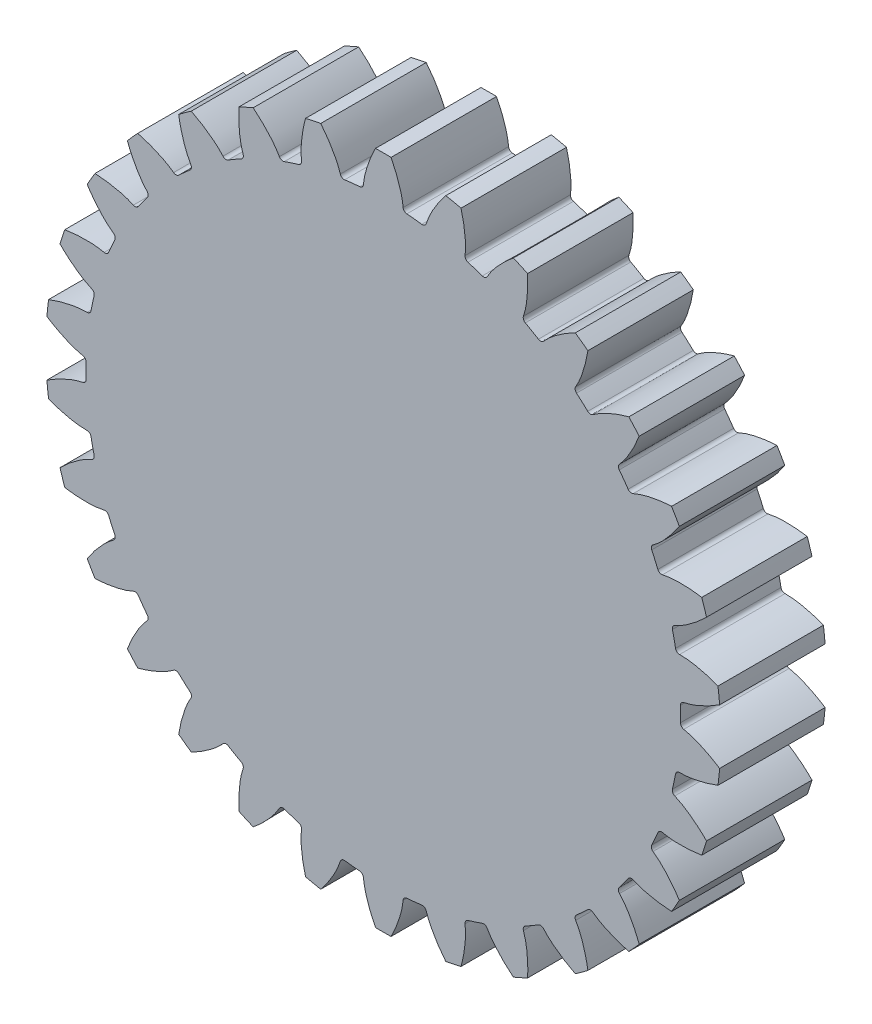
SolidWorks part; units mm, degrees
ref_plane "前视基准面" through (0, 0, 0) normal (0, 0, 1) x (1, 0, 0)
ref_plane "上视基准面" through (0, 0, 0) normal (0, 1, 0) x (1, 0, 0)
ref_plane "右视基准面" through (0, 0, 0) normal (1, 0, 0) x (0, 0, -1)
other "Configuration Table"
sketch "circles" plane through (0, 0, 0) normal (0, 0, 1) x (1, 0, 0)
  circle A0 centre (0, 0) radius 32
  circle A1 centre (0, 0) radius 27.5
  circle A2 centre (0, 0) radius 28.1908
  circle A3 centre (0, 0) radius 30
  dimension "D1" = 60
  dimension "D2" = 56.3816
  dimension "D3" = 55
  dimension "D4" = 64
extrude "Gear_extrude" add sketch "circles" along normal blind 10 contours A0
sketch "Involute" plane through (0, 0, 10) normal (0, 0, 1) x (1, 0, 0)
  spline S0 degree 4 poles (28.171, -1.0557) (28.2223, -1.0593) (28.3658, -1.0748) (28.6344, -1.1247) (29.0665, -1.2353) (29.6059, -1.4183) (30.2862, -1.7021) (31.0629, -2.0956) (31.8862, -2.5882) (32.9602, -3.3359) (34.1728, -4.337) (35.451, -5.5998) (36.7769, -7.1739) (37.9681, -8.8517) (39.0285, -10.6149) (39.9764, -12.4839) (40.7958, -14.4124) (41.4038, -16.142) (41.8493, -17.6484) (42.1713, -18.9171) (42.3998, -19.9389) (42.6495, -21.2237) (42.8522, -22.517) (43.0089, -23.8165) (43.1207, -25.1207) (43.1836, -26.1655) (43.2157, -27.0819) (43.2272, -27.8657) (43.226, -28.5232) (43.2194, -29.0333) (43.2013, -29.7091) (43.1793, -30.2472) (43.1275, -31.2203) (43.075, -31.832) (43.0114, -32.5795) (42.9682, -32.9515) (42.9431, -33.1951) (42.9309, -33.297) knots 0 0 0 0 0 0.005377 0.015084 0.028532 0.04661 0.064855 0.092111 0.119476 0.146842 0.201575 0.256307 0.307035 0.361767 0.4165 0.471232 0.525964 0.580697 0.608063 0.635429 0.662795 0.690161 0.744894 0.77226 0.799626 0.826992 0.854358 0.868042 0.881725 0.895408 0.909091 0.931818 0.954545 0.977273 0.988636 1 1 1 1 1 construction
  spline S2 degree 4 poles (28.171, 1.0557) (28.2223, 1.0593) (28.3658, 1.0748) (28.6344, 1.1247) (29.0665, 1.2353) (29.6059, 1.4183) (30.2862, 1.7021) (31.0629, 2.0956) (31.8862, 2.5882) (32.9602, 3.3359) (34.1728, 4.337) (35.451, 5.5998) (36.7769, 7.1739) (37.9681, 8.8517) (39.0285, 10.6149) (39.9764, 12.4839) (40.7958, 14.4124) (41.4038, 16.142) (41.8493, 17.6484) (42.1713, 18.9171) (42.3998, 19.9389) (42.6495, 21.2237) (42.8522, 22.517) (43.0089, 23.8165) (43.1207, 25.1207) (43.1836, 26.1655) (43.2157, 27.0819) (43.2272, 27.8657) (43.226, 28.5232) (43.2194, 29.0333) (43.2013, 29.7091) (43.1793, 30.2472) (43.1275, 31.2203) (43.075, 31.832) (43.0114, 32.5795) (42.9682, 32.9515) (42.9431, 33.1951) (42.9309, 33.297) knots 0 0 0 0 0 0.005377 0.015084 0.028532 0.04661 0.064855 0.092111 0.119476 0.146842 0.201575 0.256307 0.307035 0.361767 0.4165 0.471232 0.525964 0.580697 0.608063 0.635429 0.662795 0.690161 0.744894 0.77226 0.799626 0.826992 0.854358 0.868042 0.881725 0.895408 0.909091 0.931818 0.954545 0.977273 0.988636 1 1 1 1 1 construction
  spline S3 degree 4 poles (28.171, 1.0557) (28.2223, 1.0593) (28.3658, 1.0748) (28.6344, 1.1247) (29.0665, 1.2353) (29.6059, 1.4183) (30.2862, 1.7021) (31.0629, 2.0956) (31.8862, 2.5882) (32.9602, 3.3359) (34.1728, 4.337) (35.451, 5.5998) (36.7769, 7.1739) (37.9681, 8.8517) (39.0285, 10.6149) (39.9764, 12.4839) (40.7958, 14.4124) (41.4038, 16.142) (41.8493, 17.6484) (42.1713, 18.9171) (42.3998, 19.9389) (42.6495, 21.2237) (42.8522, 22.517) (43.0089, 23.8165) (43.1207, 25.1207) (43.1836, 26.1655) (43.2157, 27.0819) (43.2272, 27.8657) (43.226, 28.5232) (43.2194, 29.0333) (43.2078, 29.4683) (43.1997, 29.7103) (43.1953, 29.8292) knots 0 0 0 0 0 0.005377 0.015084 0.028532 0.04661 0.064855 0.092111 0.119476 0.146842 0.201575 0.256307 0.307035 0.361767 0.4165 0.471232 0.525964 0.580697 0.608063 0.635429 0.662795 0.690161 0.744894 0.77226 0.799626 0.826992 0.854358 0.868042 0.881725 0.895408 0.909091 0.909091 0.909091 0.909091 0.909091
  spline S4 degree 4 poles (28.171, -1.0557) (28.2223, -1.0593) (28.3658, -1.0748) (28.6344, -1.1247) (29.0665, -1.2353) (29.6059, -1.4183) (30.2862, -1.7021) (31.0629, -2.0956) (31.8862, -2.5882) (32.9602, -3.3359) (34.1728, -4.337) (35.451, -5.5998) (36.7769, -7.1739) (37.9681, -8.8517) (39.0285, -10.6149) (39.9764, -12.4839) (40.7958, -14.4124) (41.4038, -16.142) (41.8493, -17.6484) (42.1713, -18.9171) (42.3998, -19.9389) (42.6495, -21.2237) (42.8522, -22.517) (43.0089, -23.8165) (43.1207, -25.1207) (43.1836, -26.1655) (43.2157, -27.0819) (43.2272, -27.8657) (43.226, -28.5232) (43.2194, -29.0333) (43.2078, -29.4683) (43.1997, -29.7103) (43.1953, -29.8292) knots 0 0 0 0 0 0.005377 0.015084 0.028532 0.04661 0.064855 0.092111 0.119476 0.146842 0.201575 0.256307 0.307035 0.361767 0.4165 0.471232 0.525964 0.580697 0.608063 0.635429 0.662795 0.690161 0.744894 0.77226 0.799626 0.826992 0.854358 0.868042 0.881725 0.895408 0.909091 0.909091 0.909091 0.909091 0.909091
sketch "Db>Df" plane through (0, 0, 10) normal (0, 0, 1) x (1, 0, 0)
  line L2 (0, 0) -> (29.9589, 1.5701) construction
  line L3 (0, 0) -> (60.2478, -1.5776) construction
  line L4 (43.1953, 29.8292) -> (60.2478, -1.5776)
  line L5 (60.2478, -1.5776) -> (43.1953, -29.8292)
  circle A2 centre (0, 0) radius 30 construction
  circle A3 centre (0, 0) radius 28.1908 construction
  arc A4 (28.171, -1.0557) -> (28.171, 1.0557) centre (0, 0) ccw
  spline S0 degree 4 poles (-58.7454, -1999.1168) (17.076, -52.2104) (22.5891, -1.8433) (25.9954, -0.4491) (29.0665, -1.2353) (29.6059, -1.4183) (30.2862, -1.7021) (31.0629, -2.0956) (31.8862, -2.5882) (32.9602, -3.3359) (34.1728, -4.337) (35.451, -5.5998) (36.7769, -7.1739) (37.9681, -8.8517) (39.0285, -10.6149) (39.9764, -12.4839) (40.7958, -14.4124) (41.4038, -16.142) (41.8493, -17.6484) (42.1713, -18.9171) (42.3998, -19.9389) (42.6495, -21.2237) (42.8522, -22.517) (43.0089, -23.8165) (43.1207, -25.1207) (43.1836, -26.1655) (43.2157, -27.0819) (43.2272, -27.8657) (43.226, -28.5232) (43.1903, -31.2711) (42.8434, -36.3545) (44.7406, 23.1759) (-32.5965, -2028.0551) knots -0.284666 -0.284666 -0.284666 -0.284666 -0.284666 0.005377 0.015084 0.028532 0.04661 0.064855 0.092111 0.119476 0.146842 0.201575 0.256307 0.307035 0.361767 0.4165 0.471232 0.525964 0.580697 0.608063 0.635429 0.662795 0.690161 0.744894 0.77226 0.799626 0.826992 0.854358 0.868042 0.881725 0.895408 1.149228 1.149228 1.149228 1.149228 1.149228 only from (28.171, -1.0557) to (43.1953, -29.8292) construction
  spline S1 degree 4 poles (-58.7454, 1999.1168) (17.076, 52.2104) (22.5891, 1.8433) (25.9954, 0.4491) (29.0665, 1.2353) (29.6059, 1.4183) (30.2862, 1.7021) (31.0629, 2.0956) (31.8862, 2.5882) (32.9602, 3.3359) (34.1728, 4.337) (35.451, 5.5998) (36.7769, 7.1739) (37.9681, 8.8517) (39.0285, 10.6149) (39.9764, 12.4839) (40.7958, 14.4124) (41.4038, 16.142) (41.8493, 17.6484) (42.1713, 18.9171) (42.3998, 19.9389) (42.6495, 21.2237) (42.8522, 22.517) (43.0089, 23.8165) (43.1207, 25.1207) (43.1836, 26.1655) (43.2157, 27.0819) (43.2272, 27.8657) (43.226, 28.5232) (43.1903, 31.2711) (42.8434, 36.3545) (44.7406, -23.1759) (-32.5965, 2028.0551) knots -0.284666 -0.284666 -0.284666 -0.284666 -0.284666 0.005377 0.015084 0.028532 0.04661 0.064855 0.092111 0.119476 0.146842 0.201575 0.256307 0.307035 0.361767 0.4165 0.471232 0.525964 0.580697 0.608063 0.635429 0.662795 0.690161 0.744894 0.77226 0.799626 0.826992 0.854358 0.868042 0.881725 0.895408 1.149228 1.149228 1.149228 1.149228 1.149228 only from (28.171, 1.0557) to (43.1953, 29.8292) construction
  spline S2 degree 4 poles (28.171, -1.0557) (28.2223, -1.0593) (28.3658, -1.0748) (28.6344, -1.1247) (29.0665, -1.2353) (29.6059, -1.4183) (30.2862, -1.7021) (31.0629, -2.0956) (31.8862, -2.5882) (32.9602, -3.3359) (34.1728, -4.337) (35.451, -5.5998) (36.7769, -7.1739) (37.9681, -8.8517) (39.0285, -10.6149) (39.9764, -12.4839) (40.7958, -14.4124) (41.4038, -16.142) (41.8493, -17.6484) (42.1713, -18.9171) (42.3998, -19.9389) (42.6495, -21.2237) (42.8522, -22.517) (43.0089, -23.8165) (43.1207, -25.1207) (43.1836, -26.1655) (43.2157, -27.0819) (43.2272, -27.8657) (43.226, -28.5232) (43.2194, -29.0333) (43.2078, -29.4683) (43.1997, -29.7103) (43.1953, -29.8292) knots 0 0 0 0 0 0.005377 0.015084 0.028532 0.04661 0.064855 0.092111 0.119476 0.146842 0.201575 0.256307 0.307035 0.361767 0.4165 0.471232 0.525964 0.580697 0.608063 0.635429 0.662795 0.690161 0.744894 0.77226 0.799626 0.826992 0.854358 0.868042 0.881725 0.895408 0.909091 0.909091 0.909091 0.909091 0.909091
  spline S3 degree 4 poles (28.171, 1.0557) (28.2223, 1.0593) (28.3658, 1.0748) (28.6344, 1.1247) (29.0665, 1.2353) (29.6059, 1.4183) (30.2862, 1.7021) (31.0629, 2.0956) (31.8862, 2.5882) (32.9602, 3.3359) (34.1728, 4.337) (35.451, 5.5998) (36.7769, 7.1739) (37.9681, 8.8517) (39.0285, 10.6149) (39.9764, 12.4839) (40.7958, 14.4124) (41.4038, 16.142) (41.8493, 17.6484) (42.1713, 18.9171) (42.3998, 19.9389) (42.6495, 21.2237) (42.8522, 22.517) (43.0089, 23.8165) (43.1207, 25.1207) (43.1836, 26.1655) (43.2157, 27.0819) (43.2272, 27.8657) (43.226, 28.5232) (43.2194, 29.0333) (43.2078, 29.4683) (43.1997, 29.7103) (43.1953, 29.8292) knots 0 0 0 0 0 0.005377 0.015084 0.028532 0.04661 0.064855 0.092111 0.119476 0.146842 0.201575 0.256307 0.307035 0.361767 0.4165 0.471232 0.525964 0.580697 0.608063 0.635429 0.662795 0.690161 0.744894 0.77226 0.799626 0.826992 0.854358 0.868042 0.881725 0.895408 0.909091 0.909091 0.909091 0.909091 0.909091
  dimension "D1" = 4.5
  dimension "D2" = 60
extrude "extruded-cut1" cut sketch "Db>Df" against normal through all
fillet "fillet1" radius 0.38 2 edges at (28.171, -1.0557, 5) (28.171, 1.0557, 5)
pattern_circular "circular-parttern1" count 30 over 360 about axis through (0, 0, 10) along (0, 0, -1) of "extruded-cut1", "fillet1"
sketch "Db<Df" [suppressed] plane through (0, 0, 10) normal (0, 0, 1) x (1, 0, 0)
  line L0 (0, 0) -> (100.8439, 0) construction
  line L1 (0, 0) -> (49.9753, 1.5705) construction
  line L2 (73.0175, 48.1968) -> (100.8439, 0)
  line L3 (100.8439, 0) -> (73.0175, -48.1968)
  circle A0 centre (0, 0) radius 47.5 construction
  arc A1 (47.4927, -0.8355) -> (47.4927, 0.8355) centre (0, 0) ccw
  circle A2 centre (0, 0) radius 50 construction
  spline S0 degree 4 poles (69.1798, -1998.5936) (37.8966, 59.197) (41.8514, 1.7937) (44.8419, 0.3903) (47.7946, 0.8837) (48.4767, 1.0444) (49.3818, 1.3297) (50.5254, 1.7793) (51.8333, 2.4075) (53.2224, 3.1999) (54.6746, 4.1663) (56.0658, 5.2211) (57.3956, 6.3522) (58.6648, 7.5507) (60.1325, 9.0778) (61.7919, 11.0209) (63.5752, 13.4244) (65.4038, 16.3254) (67.0485, 19.4065) (68.4812, 22.5914) (69.5546, 25.4522) (70.3495, 27.9469) (70.9303, 30.0495) (71.3467, 31.7445) (71.7156, 33.4497) (72.0375, 35.1657) (72.3133, 36.8876) (72.5435, 38.6195) (72.7289, 40.3511) (72.8524, 41.8792) (72.9313, 43.1759) (72.9787, 44.2811) (73.0067, 45.1233) (73.0226, 46.0516) (73.0565, 49.344) (72.7733, 58.0548) (73.7264, -18.7455) (39.1601, 2047.4863) knots -0.159153 -0.159153 -0.159153 -0.159153 -0.159153 0.002688 0.005377 0.015084 0.028532 0.04661 0.064855 0.092111 0.119476 0.146842 0.174209 0.201575 0.228941 0.256307 0.307035 0.361767 0.4165 0.471232 0.525964 0.580697 0.608063 0.635429 0.662795 0.690161 0.717528 0.744894 0.77226 0.799626 0.826992 0.840675 0.854358 0.868042 0.881725 0.895408 1.086914 1.086914 1.086914 1.086914 1.086914 only from (46.9782, 0.7758) to (73.0175, 48.1968) construction
  spline S1 degree 4 poles (47.4927, 0.8355) (47.602, 0.8537) (47.9217, 0.9139) (48.5186, 1.0576) (49.3818, 1.3297) (50.5254, 1.7793) (51.8333, 2.4075) (53.2224, 3.1999) (54.6746, 4.1663) (56.0658, 5.2211) (57.3956, 6.3522) (58.6648, 7.5507) (60.1325, 9.0778) (61.7919, 11.0209) (63.5752, 13.4244) (65.4038, 16.3254) (67.0485, 19.4065) (68.4812, 22.5914) (69.5546, 25.4522) (70.3495, 27.9469) (70.9303, 30.0495) (71.3467, 31.7445) (71.7156, 33.4497) (72.0375, 35.1657) (72.3133, 36.8876) (72.5435, 38.6195) (72.7289, 40.3511) (72.8524, 41.8792) (72.9313, 43.1759) (72.9787, 44.2811) (73.0067, 45.1233) (73.0226, 46.0516) (73.0306, 46.8265) (73.0255, 47.605) (73.0207, 47.9985) (73.0175, 48.1968) knots 0.008127 0.008127 0.008127 0.008127 0.008127 0.015084 0.028532 0.04661 0.064855 0.092111 0.119476 0.146842 0.174209 0.201575 0.228941 0.256307 0.307035 0.361767 0.4165 0.471232 0.525964 0.580697 0.608063 0.635429 0.662795 0.690161 0.717528 0.744894 0.77226 0.799626 0.826992 0.840675 0.854358 0.868042 0.881725 0.895408 0.909091 0.909091 0.909091 0.909091 0.909091
  spline S2 degree 4 poles (69.1798, 1998.5936) (37.8966, -59.197) (41.8514, -1.7937) (44.8419, -0.3903) (47.7946, -0.8837) (48.4767, -1.0444) (49.3818, -1.3297) (50.5254, -1.7793) (51.8333, -2.4075) (53.2224, -3.1999) (54.6746, -4.1663) (56.0658, -5.2211) (57.3956, -6.3522) (58.6648, -7.5507) (60.1325, -9.0778) (61.7919, -11.0209) (63.5752, -13.4244) (65.4038, -16.3254) (67.0485, -19.4065) (68.4812, -22.5914) (69.5546, -25.4522) (70.3495, -27.9469) (70.9303, -30.0495) (71.3467, -31.7445) (71.7156, -33.4497) (72.0375, -35.1657) (72.3133, -36.8876) (72.5435, -38.6195) (72.7289, -40.3511) (72.8524, -41.8792) (72.9313, -43.1759) (72.9787, -44.2811) (73.0067, -45.1233) (73.0226, -46.0516) (73.0565, -49.344) (72.7733, -58.0548) (73.7264, 18.7455) (39.1601, -2047.4863) knots -0.159153 -0.159153 -0.159153 -0.159153 -0.159153 0.002688 0.005377 0.015084 0.028532 0.04661 0.064855 0.092111 0.119476 0.146842 0.174209 0.201575 0.228941 0.256307 0.307035 0.361767 0.4165 0.471232 0.525964 0.580697 0.608063 0.635429 0.662795 0.690161 0.717528 0.744894 0.77226 0.799626 0.826992 0.840675 0.854358 0.868042 0.881725 0.895408 1.086914 1.086914 1.086914 1.086914 1.086914 only from (46.9782, -0.7758) to (73.0175, -48.1968) construction
  spline S3 degree 4 poles (47.4927, -0.8355) (47.602, -0.8537) (47.9217, -0.9139) (48.5186, -1.0576) (49.3818, -1.3297) (50.5254, -1.7793) (51.8333, -2.4075) (53.2224, -3.1999) (54.6746, -4.1663) (56.0658, -5.2211) (57.3956, -6.3522) (58.6648, -7.5507) (60.1325, -9.0778) (61.7919, -11.0209) (63.5752, -13.4244) (65.4038, -16.3254) (67.0485, -19.4065) (68.4812, -22.5914) (69.5546, -25.4522) (70.3495, -27.9469) (70.9303, -30.0495) (71.3467, -31.7445) (71.7156, -33.4497) (72.0375, -35.1657) (72.3133, -36.8876) (72.5435, -38.6195) (72.7289, -40.3511) (72.8524, -41.8792) (72.9313, -43.1759) (72.9787, -44.2811) (73.0067, -45.1233) (73.0226, -46.0516) (73.0306, -46.8265) (73.0255, -47.605) (73.0207, -47.9985) (73.0175, -48.1968) knots 0.008127 0.008127 0.008127 0.008127 0.008127 0.015084 0.028532 0.04661 0.064855 0.092111 0.119476 0.146842 0.174209 0.201575 0.228941 0.256307 0.307035 0.361767 0.4165 0.471232 0.525964 0.580697 0.608063 0.635429 0.662795 0.690161 0.717528 0.744894 0.77226 0.799626 0.826992 0.840675 0.854358 0.868042 0.881725 0.895408 0.909091 0.909091 0.909091 0.909091 0.909091
  dimension "D1" = 3
  dimension "D2" = 60
extrude "extruded-cut2" [suppressed] cut sketch "Db<Df" against normal through all
fillet "fillet2" [suppressed] radius 0.38
pattern_circular "circular-parttern2" [suppressed] count 30 over 360
ref_plane "Plane2" through (0, 0, 10) normal (0, 0, 1) x (1, 0, 0)
equation "\"M\"= 2mm'模数"
equation "\"Z\" = 30'齿数"
equation "\"B\"= 10mm'齿宽"
equation "\"Alpha\"= 20\t'压力角"
equation "\"D\"= \"M\"*\"Z\"   '分度圆"
equation "\"Db\"= \"D\" * cos ( \"Alpha\" )  \t'基圆"
equation "\"Hax\"= 1'齿顶高系数"
equation "\"Cx\"= 0.25\t'顶隙系数"
equation "\"Ha\"= \"Hax\" * \"M\"\t'齿顶高"
equation "\"Hf\"= ( \"Hax\" + \"Cx\" ) * \"M\"\t'齿根高"
equation "\"Df\"= \"D\" - 2 * \"Hf\"\t\t'齿根圆"
equation "\"Da\"= \"D\" + 2 * \"Ha\"\t'齿顶圆"
equation "\"Theta\"= 360 * sqr ( ( 1 / cos ( \"Alpha\" ) ) ^ 2 - 1 ) / ( 2 * pi ) - atn ( sqr ( ( 1 / cos ( \"Alpha\" ) ) ^ 2 - 1 ) )"
equation "\"Phi\"= - ( 2 * pi * ( 90 / \"Z\" - \"Theta\" ) / 360 )"
equation "\"D1@circles\" = \"D\""
equation "\"D2@circles\" = \"Db\""
equation "\"D3@circles\" = \"Df\""
equation "\"D4@circles\" = \"Da\""
equation "\"D1@Gear_extrude\" = \"B\""
equation "\"D1@circular-parttern1\" = \"Z\""
equation "\"Db>Df\"= IIF ( \"Db\" > \"Df\" ,  unsuppressed  ,  suppressed  ) "
equation "\"extruded-cut1\"= IIF ( \"Db\" > \"Df\" ,  unsuppressed  ,  suppressed  ) "
equation "\"D1@Db<Df\"=90/\"Z\""
equation "\"D1@fillet1\" = 0.19 * \"M\""
equation "\"Db<Df\" = IIF ( \"Db\" < \"Df\" , \"unsuppressed\" , \"suppressed\" )"
equation "\"extruded-cut2\"= IIF ( \"Db\" < \"Df\" ,  unsuppressed  ,  suppressed  ) "
equation "\"D1@fillet2\" = 0.19 * \"M\""
equation "\"D1@circular-parttern2\" = \"Z\""
equation "\"circular-parttern2\"= IIF ( \"Db\" < \"Df\" ,  unsuppressed  ,  suppressed  ) "
equation "\"fillet1\"= IIF ( \"Db\" > \"Df\" ,  unsuppressed  ,  suppressed  ) "
equation "\"fillet2\"= IIF ( \"Db\" < \"Df\" ,  unsuppressed  ,  suppressed  ) "
equation "\"circular-parttern1\"= IIF ( \"Db\" > \"Df\" , \"unsuppressed\" , \"suppressed\" )"
